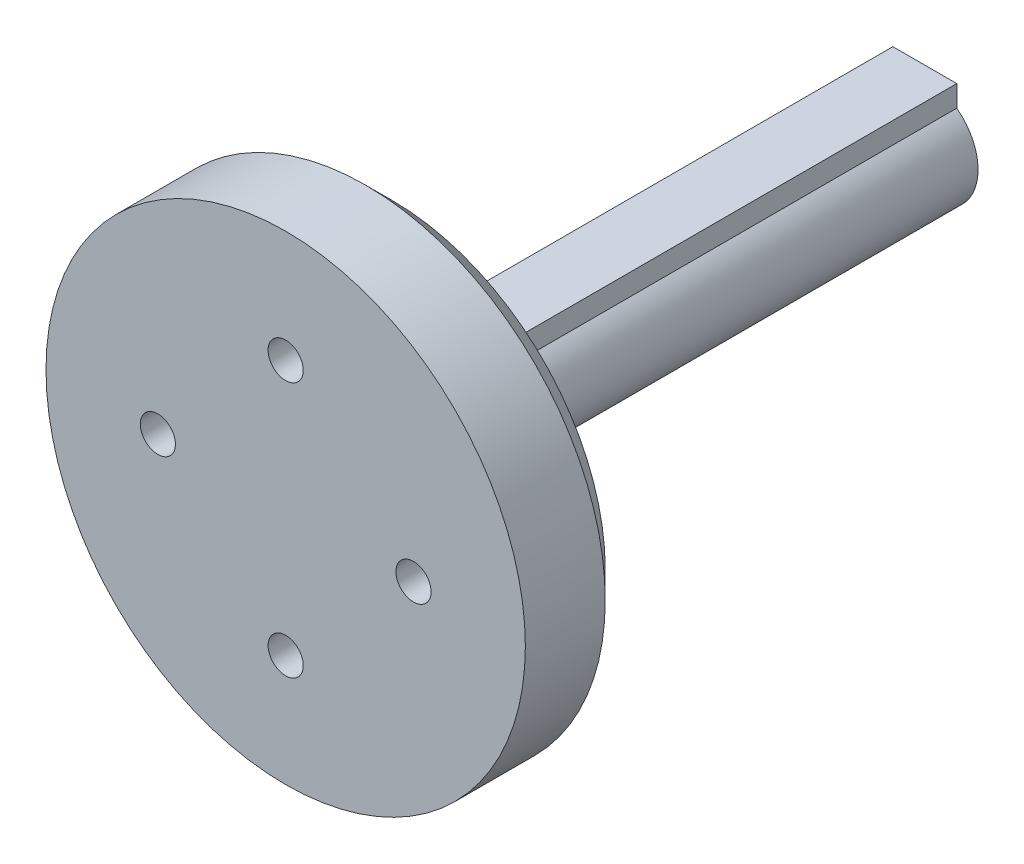
SolidWorks part; units mm, degrees
ref_plane "Front Plane" through (0, 0, 0) normal (0, 0, 1) x (1, 0, 0)
ref_plane "Top Plane" through (0, 0, 0) normal (0, 1, 0) x (1, 0, 0)
ref_plane "Right Plane" through (0, 0, 0) normal (1, 0, 0) x (0, 0, -1)
sketch "Sketch8" plane through (-41, 0, 0) normal (0, 0, -1) x (-1, 0, 0)
  line L0 (-17.5, 0) -> (-17.5, 12) construction
  line L7 (-17.5, 0) -> (-5.5, 0) construction
  line L9 (-17.5, 0) -> (-17.5, 10) construction
  arc A15 (-19.1494, 12.0447) -> (-19.0941, 11.574) centre (-17.5, 12) ccw construction
  circle A31 centre (-17.5, 12) radius 1.65
  circle A33 centre (-5.5, 0) radius 1.65
  circle A34 centre (-17.5, -12) radius 1.65
  circle A35 centre (-29.5, 0) radius 1.65
  circle A36 centre (-17.5, 0) radius 22.5
  point P26 (0, 0)
  point P29 (-17.5, 0)
  point P37 (-17.5, 0)
  dimension "D1" = 45
  dimension "D3" = 10
  dimension "D5" = 12
  dimension "D4" = 3.3
  dimension "D7" = 4
extrude "Boss-Extrude5" add sketch "Sketch8" along normal blind 10
sketch "Sketch9" plane through (0, 0, -10) normal (0, 0, -1) x (-1, 0, 0)
  circle A1 centre (23.5, 12) radius 3.65
  circle A2 centre (11.5, 0) radius 3.65
  circle A3 centre (11.5, 0) radius 3.65
  circle A4 centre (35.5, 0) radius 3.65
  circle A5 centre (23.5, -12) radius 3.65
  point P12 (23.5, 0)
  dimension "D1" = 2
  dimension "D2" = 4
extrude "Cut-Extrude1" cut sketch "Sketch9" against normal mid plane 10
sketch "Sketch10" plane through (0, 0, -10) normal (0, 0, -1) x (-1, 0, 0)
  line L0 (23.5, -12) -> (23.5, 12) construction
  line L2 (20.5, 6) -> (26.5, 6)
  line L3 (20.5, 6) -> (20.5, 4)
  line L5 (26.5, 6) -> (26.5, 4)
  line L6 (20.5, 6) -> (26.5, 4) construction
  line L7 (20.5, 4) -> (26.5, 6) construction
  arc A0 (20.5, 4) -> (26.5, 4) centre (23.5, 0) ccw
  point P6 (23.5, 5)
  dimension "D1" = 2
  dimension "D2" = 6
extrude "Boss-Extrude6" add sketch "Sketch10" along normal blind 50
fillet "Fillet1" radius 1 4 edges at (-26.5, 5, -10) (-20.5, 5, -10) (-23.5, 6, -10) (-23.5, -5, -10)
chamfer "Chamfer1" distance 2.5 angle 45 1 edges at (-46, 0, -10)
